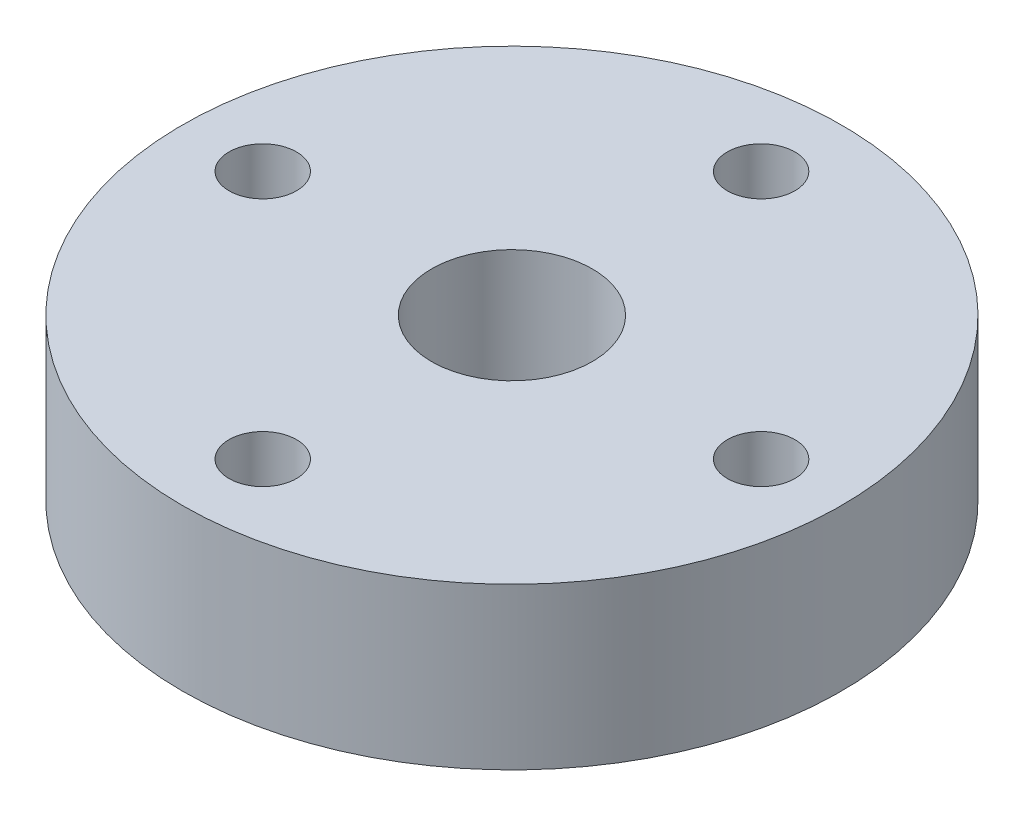
SolidWorks part; units mm, degrees
ref_plane "前视基准面" through (0, 0, 0) normal (0, 0, 1) x (1, 0, 0)
ref_plane "上视基准面" through (0, 0, 0) normal (0, 1, 0) x (1, 0, 0)
ref_plane "右视基准面" through (0, 0, 0) normal (1, 0, 0) x (0, 0, -1)
sketch "草图1" plane through (0, 0, 0) normal (0, 1, 0) x (1, 0, 0)
  circle A1 centre (0, 0) radius 5
  circle A6 centre (0, 0) radius 20.5
  circle A7 centre (0, 15.5) radius 2.1
  circle A8 centre (15.5, 0) radius 2.1
  circle A9 centre (0, -15.5) radius 2.1
  circle A10 centre (-15.5, 0) radius 2.1
  point P15 (0, 0)
  point P16 (0, 0)
  dimension "D1" = 4.2
  dimension "D2" = 10
  dimension "D3" = 15.5
  dimension "D4" = 4
  dimension "D6" = 41
extrude "凸台-拉伸1" add sketch "草图1" along normal blind 10
